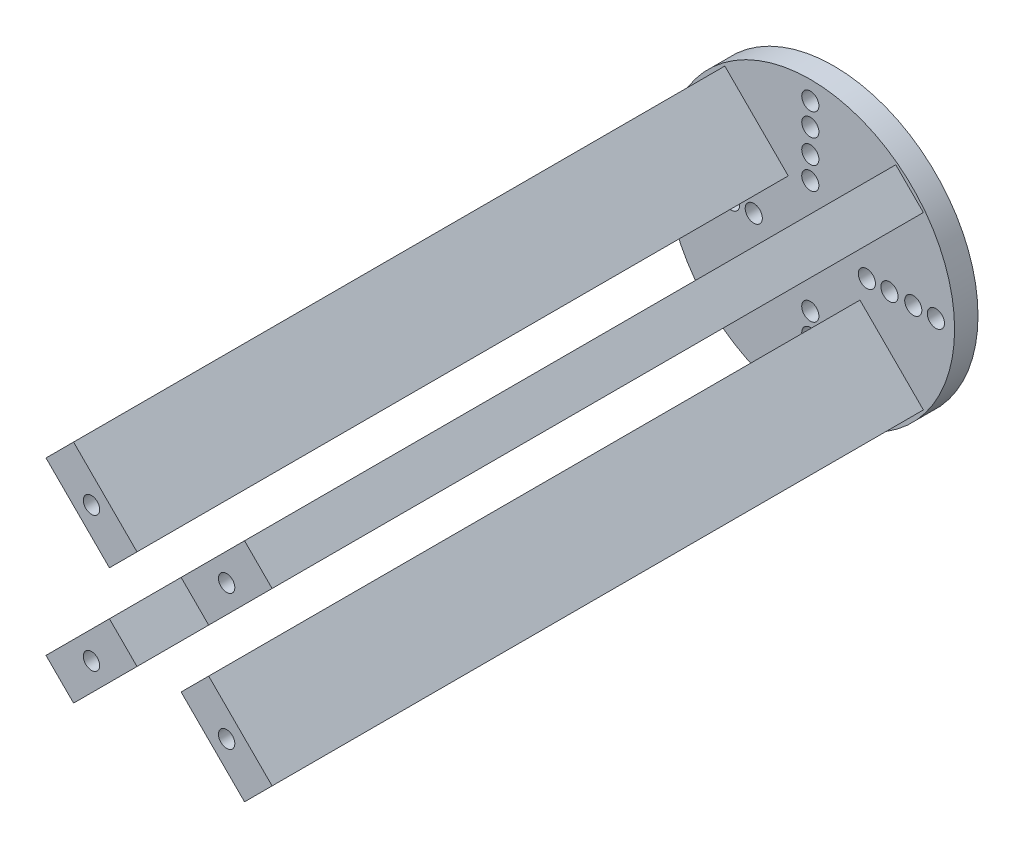
SolidWorks part; units mm, degrees
ref_plane "Ebene vorne" through (0, 0, 0) normal (0, 0, 1) x (1, 0, 0)
ref_plane "Ebene oben" through (0, 0, 0) normal (0, 1, 0) x (1, 0, 0)
ref_plane "Ebene rechts" through (0, 0, 0) normal (1, 0, 0) x (0, 0, -1)
sketch "Skizze2" plane through (0, 0, 0) normal (0, 0, 1) x (1, 0, 0)
  line L0 (0, 18.5) -> (0, -18.5)
  line L1 (-18.5, 0) -> (18.5, 0)
  circle A0 centre (0, 0) radius 18.5
  arc A1 (16.0624, -1.0994) -> (16.0624, 1.0994) centre (0, 0) ccw
  arc A2 (13.1542, -1.099) -> (13.1542, 1.099) centre (0, 0) ccw
  arc A3 (10.0904, -1.0984) -> (10.0904, 1.0984) centre (0, 0) ccw
  arc A4 (7.1666, -1.0968) -> (7.1666, 1.0968) centre (0, 0) ccw
  circle A5 centre (0, 7.25) radius 1.1
  circle A6 centre (0, 10.15) radius 1.1
  circle A7 centre (0, 13.2) radius 1.1
  circle A8 centre (0, 16.1) radius 1.1
  circle A9 centre (7.25, 0) radius 1.1
  circle A10 centre (10.15, 0) radius 1.1
  circle A11 centre (13.2, 0) radius 1.1
  circle A12 centre (16.1, 0) radius 1.1
  circle A13 centre (0, -7.25) radius 1.1
  circle A14 centre (0, -10.15) radius 1.1
  circle A15 centre (0, -13.2) radius 1.1
  circle A16 centre (0, -16.1) radius 1.1
  circle A17 centre (-7.25, 0) radius 1.1
  circle A18 centre (-10.15, 0) radius 1.1
  circle A19 centre (-13.2, 0) radius 1.1
  circle A20 centre (-16.1, 0) radius 1.1
  arc A21 (1.0968, 7.1666) -> (-1.0968, 7.1666) centre (0, 0) ccw
  arc A22 (1.0984, 10.0904) -> (-1.0984, 10.0904) centre (0, 0) ccw
  arc A23 (1.099, 13.1542) -> (-1.099, 13.1542) centre (0, 0) ccw
  arc A24 (1.0994, 16.0624) -> (-1.0994, 16.0624) centre (0, 0) ccw
  arc A25 (-7.1666, 1.0968) -> (-7.1666, -1.0968) centre (0, 0) ccw
  arc A26 (-10.0904, 1.0984) -> (-10.0904, -1.0984) centre (0, 0) ccw
  arc A27 (-13.1542, 1.099) -> (-13.1542, -1.099) centre (0, 0) ccw
  arc A28 (-16.0624, 1.0994) -> (-16.0624, -1.0994) centre (0, 0) ccw
  arc A29 (-1.0968, -7.1666) -> (1.0968, -7.1666) centre (0, 0) ccw
  arc A30 (-1.0984, -10.0904) -> (1.0984, -10.0904) centre (0, 0) ccw
  arc A31 (-1.099, -13.1542) -> (1.099, -13.1542) centre (0, 0) ccw
  arc A32 (-1.0994, -16.0624) -> (1.0994, -16.0624) centre (0, 0) ccw
  point P46 (0, 0)
  dimension "D1" = 37
  dimension "D2" = 32.2
  dimension "D3" = 26.4
  dimension "D4" = 20.3
  dimension "D5" = 14.5
  dimension "D6" = 2.2
  dimension "D7" = 4
extrude "Aufsatz-Linear austragen1" add sketch "Skizze2" along normal blind 3 contours A12 L1 A0 L0 A8 A7 A6 A5 A9 A10 A11 | A16 L0 A0 L1 A12 A11 A10 A9 A13 A14 A15 | A20 L1 A0 L0 A16 A15 A14 A13 A17 A18 A19 | A20 L1 A19 A18 A17 L0 A5 A6 A7 A8 A0
sketch "Skizze4" plane through (0, 0, 3) normal (0, 0, 1) x (1, 0, 0)
  line L0 (0, 0) -> (13.0815, 13.0815) construction
  line L1 (2.8284, 6.364) -> (10.9602, 14.4957)
  line L2 (2.8284, 6.364) -> (6.364, 2.8284)
  line L3 (10.9602, 14.4957) -> (14.4957, 10.9602)
  line L4 (6.364, 2.8284) -> (14.4957, 10.9602)
  line L5 (0, 0) -> (18.5, 0) construction
  line L6 (6.364, -2.8284) -> (14.4957, -10.9602)
  line L7 (6.364, -2.8284) -> (2.8284, -6.364)
  line L8 (2.8284, -6.364) -> (10.9602, -14.4957)
  line L9 (14.4957, -10.9602) -> (10.9602, -14.4957)
  line L10 (-2.8284, -6.364) -> (-10.9602, -14.4957)
  line L11 (-2.8284, -6.364) -> (-6.364, -2.8284)
  line L12 (-6.364, -2.8284) -> (-14.4957, -10.9602)
  line L13 (-10.9602, -14.4957) -> (-14.4957, -10.9602)
  line L14 (-6.364, 2.8284) -> (-14.4957, 10.9602)
  line L15 (-6.364, 2.8284) -> (-2.8284, 6.364)
  line L16 (-2.8284, 6.364) -> (-10.9602, 14.4957)
  line L17 (-14.4957, 10.9602) -> (-10.9602, 14.4957)
  circle A0 centre (0, 0) radius 18.5 construction
  point P26 (0, 0)
  dimension "D1" = 2.5
  dimension "D2" = 45
  dimension "D3" = 11.5
  dimension "D4" = 6.5
  dimension "D5" = 2.5
  dimension "D6" = 4
extrude "Aufsatz-Linear austragen2" add sketch "Skizze4" along normal blind 83.5
sketch "Skizze5" plane through (0, 0, 86.5) normal (0, 0, 1) x (1, 0, 0)
  line L0 (-6.364, -2.8284) -> (-10.9602, -14.4957) construction
  line L1 (-2.8284, -6.364) -> (-6.364, -2.8284) construction
  line L2 (-6.364, -2.8284) -> (-14.4957, -10.9602) construction
  line L3 (-10.9602, -14.4957) -> (-14.4957, -10.9602) construction
  line L4 (-2.8284, -6.364) -> (-14.4957, -10.9602) construction
  circle A0 centre (-8.6621, -8.6621) radius 1.05
  circle A1 centre (-8.6621, 8.6621) radius 1.05
  circle A2 centre (8.6621, 8.6621) radius 1.05
  circle A3 centre (8.6621, -8.6621) radius 1.05
  point P22 (0, 0)
  dimension "D1" = 2.1
  dimension "D2" = 4
extrude "Schnitt-Linear austragen2" cut sketch "Skizze5" against normal blind 13
